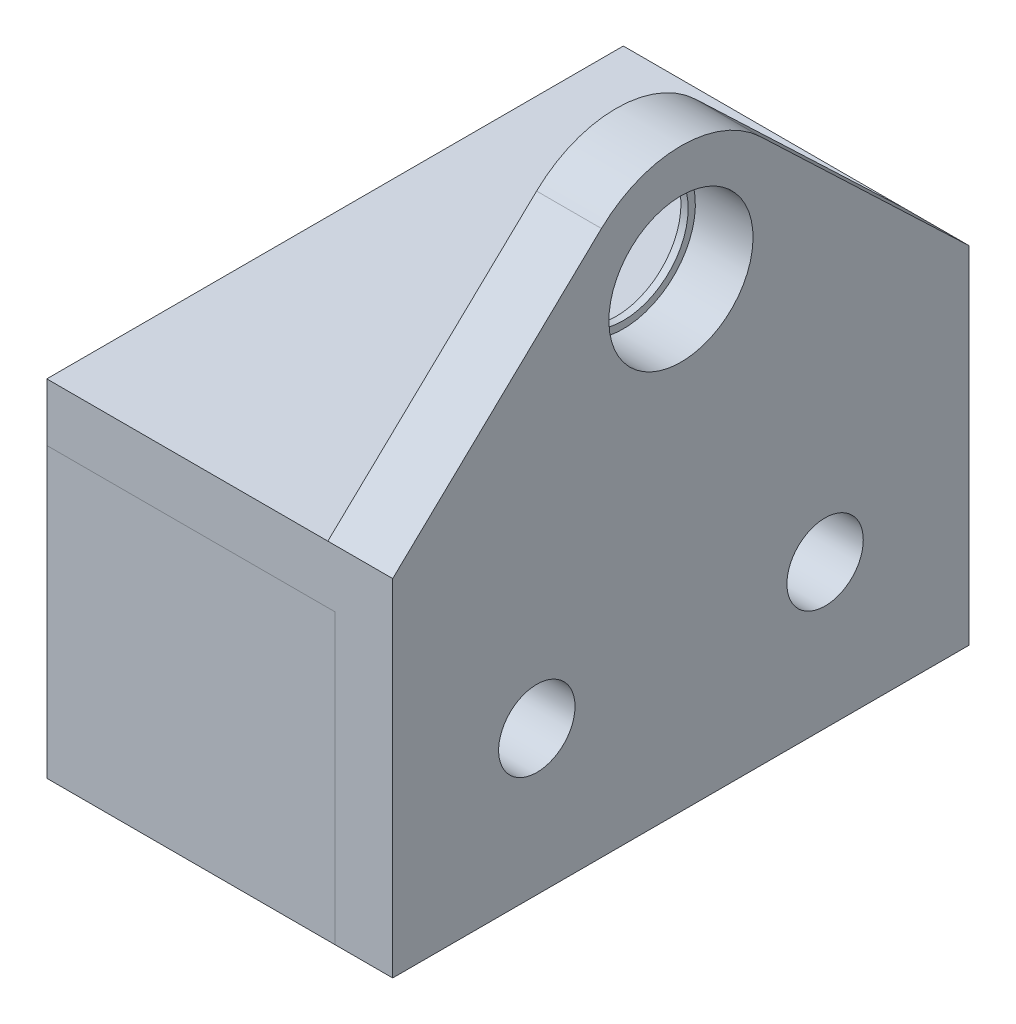
SolidWorks part; units mm, degrees
material "ABS"
ref_plane "Спереди" through (0, 0, 0) normal (0, 0, 1) x (1, 0, 0)
ref_plane "Сверху" through (0, 0, 0) normal (0, 1, 0) x (1, 0, 0)
ref_plane "Справа" through (0, 0, 0) normal (1, 0, 0) x (0, 0, -1)
sketch "Эскиз2" plane through (0, 0, 0) normal (0, 0, 1) x (1, 0, 0)
  line L1 (10, -10) -> (-10, -10)
  line L2 (10, -10) -> (10, 10)
  line L3 (10, 10) -> (-10, 10)
  line L4 (-10, -10) -> (-10, 10)
  line L5 (10, -10) -> (-10, 10) construction
  line L6 (10, 10) -> (-10, -10) construction
  point P0 (0, 0)
  dimension "D1" = 20
  dimension "D2" = 20
extrude "Бобышка-Вытянуть1" add sketch "Эскиз2" along normal mid plane 40
sketch "Эскиз3" plane through (10, 0, 0) normal (1, 0, 0) x (0, 0, -1)
  line L1 (-20, 10) -> (20, 10)
  line L2 (-20, 10) -> (20, 10) construction
  line L3 (-20, 10) -> (-20, 14)
  line L4 (-20, 14) -> (20, 14)
  line L5 (-20, 10) -> (20, 10)
  line L6 (20, 10) -> (20, 14)
  line L7 (20, -10) -> (20, 10)
  line L8 (20, 10) -> (-20, 10)
  line L9 (-20, 10) -> (-20, -10)
  line L10 (-20, -10) -> (20, -10)
  line L11 (20, -10) -> (20, 10)
  line L12 (0, 14) -> (0, 10) construction
  line L13 (-20, 10) -> (-20, -10)
  line L14 (-20, -10) -> (20, -10)
  line L15 (-20, 12) -> (20, 12) construction
  point P224 (0, 12)
  dimension "D1" = 4
  dimension "D3" = 0
extrude "Бобышка-Вытянуть2" add sketch "Эскиз3" along normal blind 4 separate body
hole_wizard "Отверстие с зазором M51" positions "Эскиз4" profile "Эскиз5" hole size "M5" standard "ISO" end condition up to next
sketch "Эскиз4" plane through (14, 0, 0) normal (1, 0, 0) x (0, 0, -1)
  point P0 (-10, 0)
  point P2 (10, 0)
  dimension "D1" = 20
  dimension "D2" = 10
sketch "Эскиз5" plane through (14, 0, 10) normal (0, 1, 0) x (0, 0, -1)
  line L0 (0, 0) -> (0, 24)
  line L1 (0, 24) -> (2.65, 24)
  line L2 (2.65, 24) -> (2.65, 0)
  line L5 (2.65, 0) -> (0, 0)
  line L11 (0, -6.35) -> (0, 107.95) construction
  dimension "Диаметр сквозного отверстия" = 5.3
  dimension "Глубина сквозного отверстия" = 24
sketch "Эскиз6" plane through (10, 0, 0) normal (-1, 0, 0) x (0, 0, 1)
  line L0 (-20, -10) -> (-20, 14) construction
  line L1 (20, 14) -> (-20, 14)
  line L3 (20, 14) -> (20, 10)
  line L5 (20, 10) -> (-20, 10)
  line L6 (-20, 14) -> (-20, 10)
  line L7 (0, 10) -> (0, 14) construction
  line L8 (20, 12) -> (-20, 12) construction
  point P242 (0, 12)
  dimension "D1" = 4
extrude "Бобышка-Вытянуть3" add sketch "Эскиз6" along normal blind 20
sketch "Эскиз7" plane through (0, 10, 0) normal (0, -1, 0) x (1, 0, 0)
  line L0 (0, 0) -> (-50000, 0) construction
  line L1 (-3.05, 8) -> (3.05, 8)
  line L2 (-3.05, 8) -> (-3.05, 16)
  line L3 (-3.05, 16) -> (3.05, 16)
  line L4 (3.05, 8) -> (3.05, 16)
  line L5 (0, 16) -> (0, 8) construction
  line L6 (-3.05, 12) -> (3.05, 12) construction
  line L7 (-3.05, -12) -> (3.05, -12) construction
  line L8 (0, -16) -> (0, -8) construction
  line L9 (3.05, -8) -> (3.05, -16)
  line L10 (-3.05, -16) -> (3.05, -16)
  line L11 (-3.05, -8) -> (-3.05, -16)
  line L12 (-3.05, -8) -> (3.05, -8)
  point P14 (0, -12)
  point P56 (0, 12)
  dimension "D1" = 6.1
  dimension "D2" = 8
  dimension "D3" = 12
extrude "Бобышка-Вытянуть4" add sketch "Эскиз7" along normal blind 3
chamfer "Фаска1" distance 1 angle 45 4 edges at (-3.05, 7, 12) (3.05, 7, 12) (3.05, 7, -12) (-3.05, 7, -12)
sketch "Эскиз8" plane through (14, 0, 0) normal (1, 0, 0) x (0, 0, -1)
  line L0 (-20, 14) -> (-5.5172, 27.7931)
  line L1 (5.5172, 27.7931) -> (20, 14)
  line L2 (-20, 14) -> (20, 14) construction
  circle A0 centre (0, 22) radius 5
  arc A1 (-5.5172, 27.7931) -> (5.5172, 27.7931) centre (0, 22) cw
  line M8 (20, 14) -> (-20, 14)
  dimension "D1" = 10
  dimension "D2" = 3
  dimension "D3" = 3
extrude "Бобышка-Вытянуть5" add sketch "Эскиз8" against normal blind 4.5 contours A1 L0 L1 A0 M8
sketch "Эскиз9" plane through (9.5, 0, 0) normal (-1, 0, 0) x (0, 0, 1)
  circle A0 centre (0, 22) radius 5 construction
  circle A1 centre (0, 22) radius 5
  circle A2 centre (0, 22) radius 4.5
  dimension "D1" = 0.5
extrude "Бобышка-Вытянуть6" add sketch "Эскиз9" against normal offset from surface (0.5 mm away) 4 up to face at (14, 0, 7.35)
